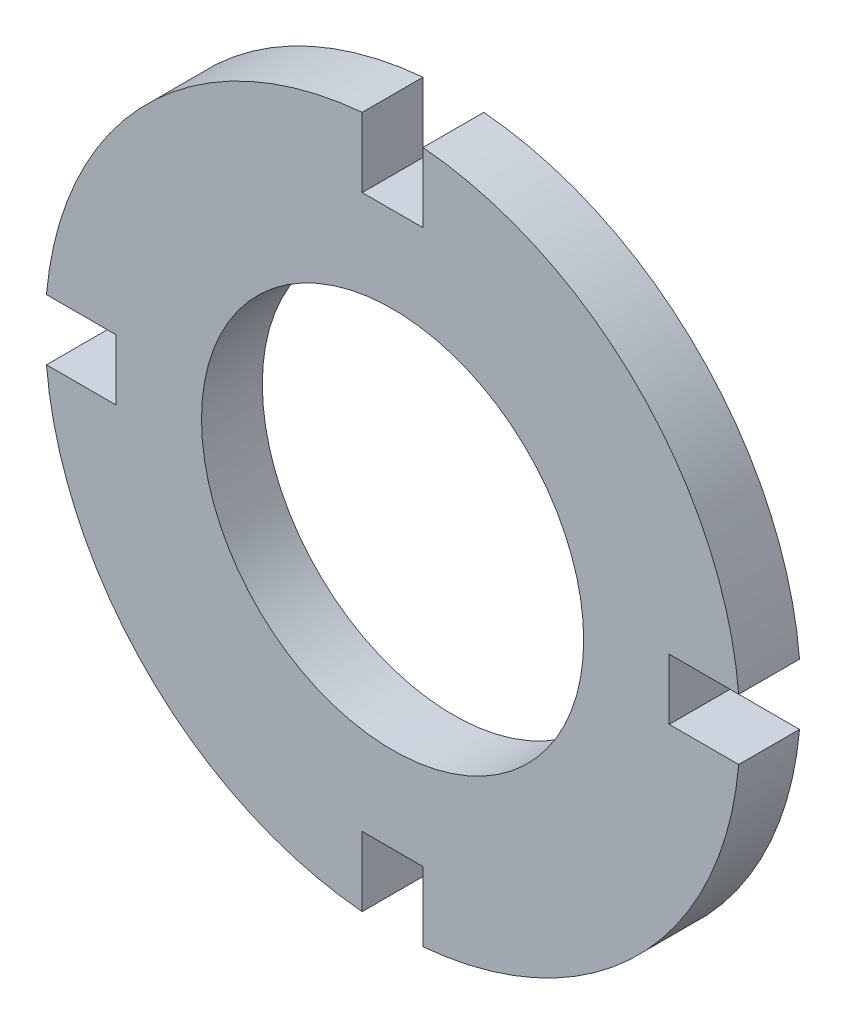
SolidWorks part; units mm, degrees
ref_plane "Front Plane" through (0, 0, 0) normal (0, 0, 1) x (1, 0, 0)
ref_plane "Top Plane" through (0, 0, 0) normal (0, 1, 0) x (1, 0, 0)
ref_plane "Right Plane" through (0, 0, 0) normal (1, 0, 0) x (0, 0, -1)
sketch "Sketch1" plane through (0, 0, 0) normal (0, 0, 1) x (1, 0, 0)
  line L2 (25.3026, -2.2225) -> (20.2226, -2.2225)
  line L3 (-25.3026, 2.2225) -> (-20.2226, 2.2225)
  line L5 (-25.3026, -2.2225) -> (-20.2226, -2.2225)
  line L6 (25.3026, 2.2225) -> (20.2226, 2.2225)
  line L7 (20.2226, -2.2225) -> (20.2226, 2.2225)
  line L8 (-20.2226, 2.2225) -> (-20.2226, -2.2225)
  line L9 (-2.2225, 25.3026) -> (-2.2225, 20.2226)
  line L10 (-2.2225, 20.2226) -> (2.2225, 20.2226)
  line L11 (2.2225, 25.3026) -> (2.2225, 20.2226)
  line L12 (-2.2225, -25.3026) -> (-2.2225, -20.2226)
  line L13 (-2.2225, -20.2226) -> (2.2225, -20.2226)
  line L14 (2.2225, -25.3026) -> (2.2225, -20.2226)
  arc A0 (-25.3026, -2.2225) -> (-2.2225, -25.3026) centre (0, 0) ccw
  circle A1 centre (0, 0) radius 13.97
  arc A2 (25.3026, 2.2225) -> (2.2225, 25.3026) centre (0, 0) ccw
  arc A3 (-2.2225, 25.3026) -> (-25.3026, 2.2225) centre (0, 0) ccw
  arc A4 (2.2225, -25.3026) -> (25.3026, -2.2225) centre (0, 0) ccw
  dimension "D1" = 50.8
  dimension "D2" = 27.94
  dimension "D3" = 5.08
  dimension "D4" = 4.445
  dimension "D5" = 5.08
  dimension "D6" = 5.08
  dimension "D7" = 5.08
  dimension "D8" = 4.445
  dimension "D9" = 5.08
  dimension "D10" = 4.445
  dimension "D11" = 5.08
  dimension "D12" = 5.08
  dimension "D13" = 4.445
  dimension "D14" = 5.08
extrude "Boss-Extrude1" add sketch "Sketch1" along normal blind 4.445
